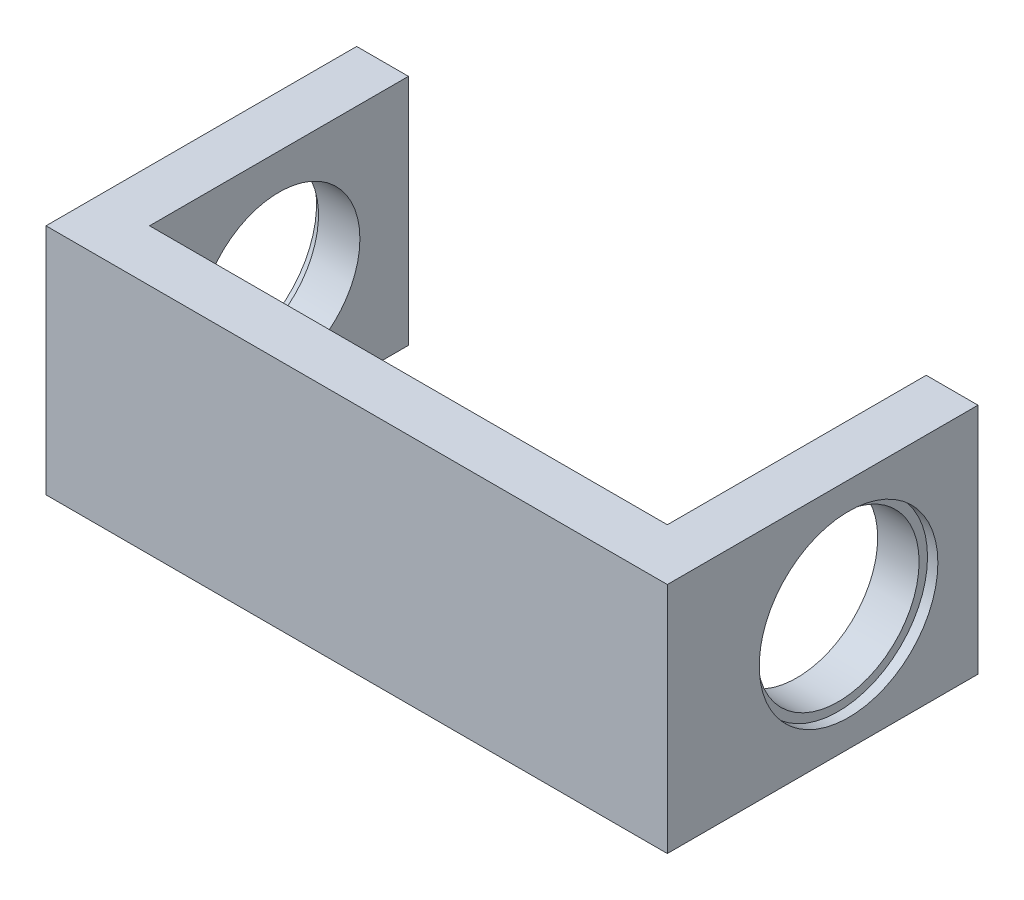
SolidWorks part; units mm, degrees
ref_plane "Front Plane" through (0, 0, 0) normal (0, 0, 1) x (1, 0, 0)
ref_plane "Top Plane" through (0, 0, 0) normal (0, 1, 0) x (1, 0, 0)
ref_plane "Right Plane" through (0, 0, 0) normal (1, 0, 0) x (0, 0, -1)
sketch "Sketch1" plane through (0, 0, 0) normal (0, 1, 0) x (1, 0, 0)
  line L0 (0, 25.4) -> (0, 0)
  line L1 (0, 0) -> (50.8, 0)
  line L2 (50.8, 0) -> (50.8, 25.4)
  dimension "D1" = 25.4
  dimension "D2" = 50.8
  dimension "D3" = 25.4
extrude "Extrude-Thin1" add sketch "Sketch1" along normal blind 22.86 thin
hole_wizard "CBORE for #6 Socket Head Cap Screw1" positions "Sketch2" profile "Sketch3" counterbore size "#6" standard "ANSI Inch"
sketch "Sketch2" plane through (55.88, 0, 0) normal (1, 0, 0) x (0, 0, -1)
  line L0 (25.4, 11.43) -> (12.7, 11.43) construction
  line L1 (25.4, 22.86) -> (25.4, 0) construction
  point P0 (12.7, 11.43)
  dimension "D1" = 12.7
sketch "Sketch3" plane through (55.88, 11.43, -12.7) normal (0, 1, 0) x (0, 0, -1)
  line L0 (0, 0) -> (0, 5.08)
  line L1 (0, 5.08) -> (7.9375, 5.08)
  line L3 (7.9375, 5.08) -> (7.9375, 1.016)
  line L4 (7.9375, 1.016) -> (8.763, 1.016)
  line L5 (8.763, 1.016) -> (8.763, 0)
  line L7 (8.763, 0) -> (0, 0)
  line L11 (0, -6.35) -> (0, 107.95) construction
  dimension "Thru Hole Dia." = 15.875
  dimension "Thru Hole Depth" = 5.08
  dimension "C'Bore Dia." = 17.526
  dimension "C'Bore Depth" = 1.016
hole_wizard "CBORE for #6 Socket Head Cap Screw2" positions "Sketch4" profile "Sketch5" counterbore size "#6" standard "ANSI Inch" end condition up to next
sketch "Sketch4" plane through (-5.08, 0, 0) normal (-1, 0, 0) x (0, 0, 1)
  line L0 (-12.7, 11.43) -> (-25.4, 11.43) construction
  line L3 (-25.4, 22.86) -> (-25.4, 0) construction
  point P16 (-12.7, 11.43)
  dimension "D1" = 12.7
sketch "Sketch5" plane through (-5.08, 11.43, -12.7) normal (0, 1, 0) x (0, 0, 1)
  line L0 (0, 0) -> (0, 5.08)
  line L1 (0, 5.08) -> (7.9375, 5.08)
  line L3 (7.9375, 5.08) -> (7.9375, 1.016)
  line L4 (7.9375, 1.016) -> (8.763, 1.016)
  line L5 (8.763, 1.016) -> (8.763, 0)
  line L7 (8.763, 0) -> (0, 0)
  line L11 (0, -6.35) -> (0, 107.95) construction
  dimension "Thru Hole Dia." = 15.875
  dimension "Thru Hole Depth" = 5.08
  dimension "C'Bore Dia." = 17.526
  dimension "C'Bore Depth" = 1.016
